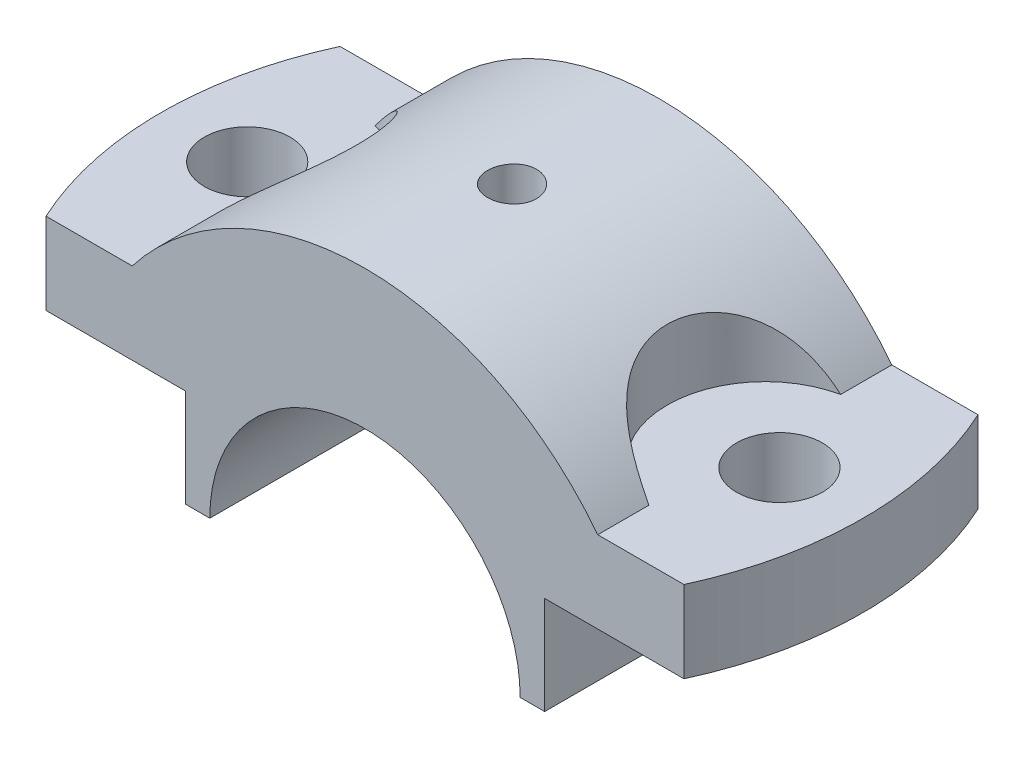
SolidWorks part; units mm, degrees
ref_plane "Front Plane" through (0, 0, 0) normal (0, 0, 1) x (1, 0, 0)
ref_plane "Top Plane" through (0, 0, 0) normal (0, 1, 0) x (1, 0, 0)
ref_plane "Right Plane" through (0, 0, 0) normal (1, 0, 0) x (0, 0, -1)
sketch "Sketch1" plane through (0, 0, 0) normal (0, 0, 1) x (1, 0, 0)
  line L0 (-22, 0) -> (-19, 0)
  line L11 (-43, 22) -> (-43, 12)
  line L13 (43, 22) -> (43, 12)
  line L14 (-22, 12) -> (-22, 0)
  line L15 (-22, 12) -> (-43, 12)
  line L17 (-43, 22) -> (-28.4956, 22)
  line L19 (43, 22) -> (28.4956, 22)
  line L20 (22, 12) -> (22, 0)
  line L21 (22, 12) -> (43, 12)
  line L23 (19, 0) -> (22, 0)
  arc A0 (19, 0) -> (-19, 0) centre (0, 0) ccw
  arc A1 (28.4956, 22) -> (-28.4956, 22) centre (0, 0) ccw
  point P18 (22, 0)
extrude "Boss-Extrude1" add sketch "Sketch1" against normal blind 36
ref_plane "Plane1" through (0, 22, 0) normal (0, 1, 0) x (1, 0, 0)
sketch "Sketch2" plane through (0, 22, 0) normal (0, 1, 0) x (1, 0, 0)
  line L0 (-43, 36) -> (-43, 0)
  line L1 (-43, 0) -> (-39.0512, 0)
  line L2 (-28.4956, 0) -> (-43, 0) construction
  line L3 (-43, 36) -> (-39.0512, 36)
  line L4 (-28.4956, 36) -> (-43, 36) construction
  line L5 (39.0512, 36) -> (43, 36)
  line L6 (43, 36) -> (43, 0)
  line L7 (43, 36) -> (43, 0) construction
  line L8 (39.0512, 0) -> (43, 0)
  line L9 (43, 0) -> (28.4956, 0) construction
  arc A0 (-39.0512, 36) -> (-39.0512, 0) centre (0, 18) ccw
  arc A1 (39.0512, 0) -> (39.0512, 36) centre (0, 18) ccw
extrude "Cut-Extrude1" cut sketch "Sketch2" against normal blind 36 contours A0 L3 L0 | A0 L0 L1 | A1 L6 L5 | A1 L8 L6
sketch "Sketch3" plane through (0, 22, 0) normal (0, 1, 0) x (1, 0, 0)
  line L1 (0, 36) -> (0, -3.0051)
  line L2 (28.4956, 36) -> (-28.4956, 36) construction
  circle A3 centre (-31, 18) radius 12
  circle A4 centre (31, 18) radius 12
extrude "Cut-Extrude10" cut sketch "Sketch3" along normal through all contours A3 | A4
sketch "Sketch9" plane through (0, 22, 0) normal (0, 1, 0) x (1, 0, 0)
  circle A4 centre (-32.5007, 18.0849) radius 5.25
  circle A5 centre (32.4991, 18.2428) radius 5.25
ref_plane "Plane4" through (0, 36, 0) normal (0, 1, 0) x (1, 0, 0)
sketch "Sketch10" plane through (0, 36, 0) normal (0, 1, 0) x (1, 0, 0)
  circle A0 centre (0, 18) radius 3
extrude "Cut-Extrude12" cut sketch "Sketch10" against normal blind 10
sketch "Sketch11" plane through (0, 22, 0) normal (0, 1, 0) x (1, 0, 0)
  circle A0 centre (0, 18) radius 1.5
extrude "Cut-Extrude13" cut sketch "Sketch11" against normal through all both and the other way through all
extrude "Cut-Extrude14" cut sketch "Sketch9" against normal blind 10
